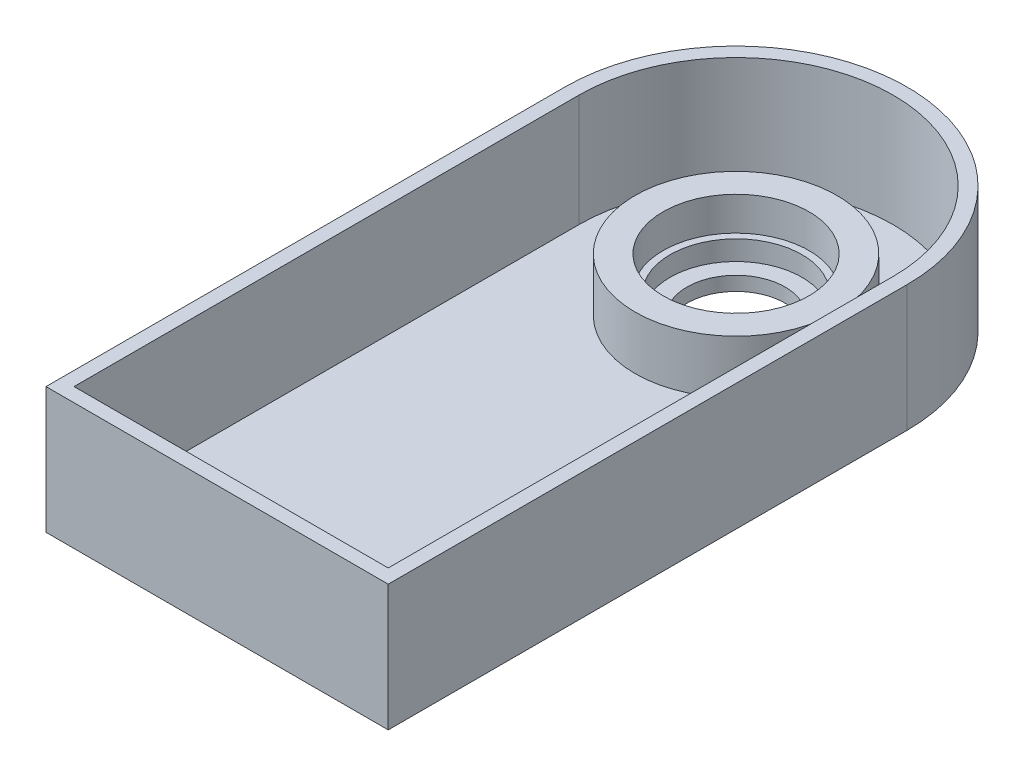
SolidWorks part; units mm, degrees
ref_plane "Front Plane" through (0, 0, 0) normal (0, 0, 1) x (1, 0, 0)
ref_plane "Top Plane" through (0, 0, 0) normal (0, 1, 0) x (1, 0, 0)
ref_plane "Right Plane" through (0, 0, 0) normal (1, 0, 0) x (0, 0, -1)
sketch "Sketch1" plane through (0, 0, 0) normal (0, 1, 0) x (1, 0, 0)
  line L8 (61, 2) -> (61, -133)
  line L11 (117, 2) -> (117, -178)
  line L12 (5, -178) -> (117, -178)
  line L14 (5, 2) -> (5, -178)
  line L15 (122, -183) -> (0, -183)
  line L16 (0, -183) -> (0, 2)
  line L17 (122, -183) -> (122, 2)
  circle A2 centre (61, 2) radius 36
  arc A3 (0, 2) -> (122, 2) centre (61, 2) cw
  arc A4 (5, 2) -> (117, 2) centre (61, 2) cw
extrude "Boss-Extrude2" add sketch "Sketch1" along normal blind 5
sketch "Sketch3" plane through (0, 5, 0) normal (0, 1, 0) x (1, 0, 0)
  line L0 (5, -178) -> (117, -178)
  line L1 (117, -178) -> (117, 2)
  line L2 (5, -178) -> (5, 2)
  arc A0 (5, 2) -> (117, 2) centre (61, 2) cw
  arc M1 (122, 2) -> (0, 2) centre (61, 2) ccw
  line M2 (0, 2) -> (0, -183)
  line M3 (0, -183) -> (122, -183)
  line M4 (122, -183) -> (122, 2)
extrude "Boss-Extrude3" add sketch "Sketch3" along normal blind 40 contours L2 A0 L1 L0 M4 M1 M2 M3
sketch "Sketch4" plane through (0, 5, 0) normal (0, 1, 0) x (1, 0, 0)
  circle A0 centre (61, 2) radius 17.5
  dimension "D1" = 35
extrude "Cut-Extrude1" cut sketch "Sketch4" against normal blind 40
sketch "Sketch5" plane through (0, 5, 0) normal (0, 1, 0) x (1, 0, 0)
  circle A0 centre (61, 2) radius 23.5
  circle A1 centre (61, 2) radius 26
  dimension "D1" = 47
extrude "Boss-Extrude4" add sketch "Sketch5" along normal blind 7
sketch "Sketch6" plane through (0, 5, 0) normal (0, 1, 0) x (1, 0, 0)
  circle A0 centre (61, 2) radius 36
  circle M1 centre (61, 2) radius 26
extrude "Boss-Extrude5" add sketch "Sketch6" along normal blind 19 contours A0 M1
